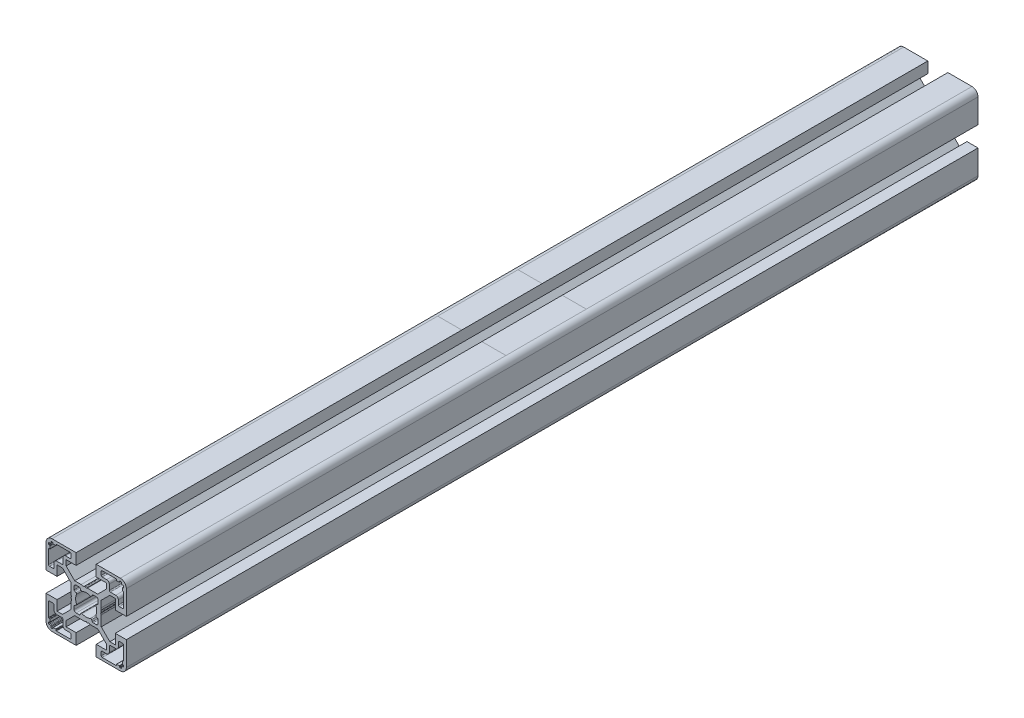
SolidWorks part; units mm, degrees
material "6063-T5"
ref_plane "Front Plane" through (0, 0, 0) normal (0, 0, 1) x (1, 0, 0)
ref_plane "Top Plane" through (0, 0, 0) normal (0, 1, 0) x (1, 0, 0)
ref_plane "Right Plane" through (0, 0, 0) normal (1, 0, 0) x (0, 0, -1)
ref_plane "Plan1" through (0, 0, 50) normal (0, 0, 1) x (1, 0, 0)
sketch "Esquisse1" plane through (0, 0, 50) normal (0, 0, 1) x (1, 0, 0)
  line L0 (-11.2645, -4.6769) -> (-11.2645, 2.1231)
  line L1 (-10.7645, 2.6231) -> (-9.0645, 2.6231)
  line L2 (-8.5645, 2.1231) -> (-8.5645, -0.0769)
  line L3 (-7.2645, -1.3769) -> (-4.5645, -1.3769)
  line L4 (-4.0645, -1.8769) -> (-4.0645, -4.5769)
  line L5 (-2.7645, -5.8769) -> (-0.5645, -5.8769)
  line L6 (-0.0645, -6.3769) -> (-0.0645, -8.0769)
  line L7 (-0.5645, -8.5769) -> (-7.3645, -8.5769)
  line L8 (-7.5645, -8.3769) -> (-7.5645, -8.0769)
  line L9 (-7.7645, -7.8769) -> (-8.9645, -7.8769)
  line L10 (-9.1645, -8.0769) -> (-9.1645, -8.3769)
  line L11 (-9.3645, -8.5769) -> (-9.8645, -8.5769)
  line L12 (-10.1645, -8.2769) -> (-10.1645, -7.7769)
  line L13 (-10.4645, -7.4769) -> (-10.9645, -7.4769)
  line L14 (-11.2645, -7.1769) -> (-11.2645, -6.6769)
  line L15 (-11.0645, -6.4769) -> (-10.7645, -6.4769)
  line L16 (-10.5645, -6.2769) -> (-10.5645, -5.0769)
  line L17 (-10.7645, -4.8769) -> (-11.0645, -4.8769)
  line L18 (14.9355, -8.0769) -> (14.9355, -6.3769)
  line L19 (15.4355, -5.8769) -> (17.6355, -5.8769)
  line L20 (18.9355, -4.5769) -> (18.9355, -1.8769)
  line L21 (19.4355, -1.3769) -> (22.1355, -1.3769)
  line L22 (23.4355, -0.0769) -> (23.4355, 2.1231)
  line L23 (23.9355, 2.6231) -> (25.6355, 2.6231)
  line L24 (26.1355, 2.1231) -> (26.1355, -4.6769)
  line L25 (25.9355, -4.8769) -> (25.6355, -4.8769)
  line L26 (25.4355, -5.0769) -> (25.4355, -6.2769)
  line L27 (25.6355, -6.4769) -> (25.9355, -6.4769)
  line L28 (26.1355, -6.6769) -> (26.1355, -7.1769)
  line L29 (25.8355, -7.4769) -> (25.3355, -7.4769)
  line L30 (25.0355, -7.7769) -> (25.0355, -8.2769)
  line L31 (24.7355, -8.5769) -> (24.2355, -8.5769)
  line L32 (24.0355, -8.3769) -> (24.0355, -8.0769)
  line L33 (23.8355, -7.8769) -> (22.6355, -7.8769)
  line L34 (22.4355, -8.0769) -> (22.4355, -8.3769)
  line L35 (22.2355, -8.5769) -> (15.4355, -8.5769)
  line L36 (-12.5645, 27.1231) -> (-12.5645, 15.1231)
  line L37 (-12.5645, 15.1231) -> (-7.0645, 15.1231)
  line L38 (-7.0645, 15.1231) -> (-7.0645, 20.1231)
  line L39 (-7.0645, 20.1231) -> (-4.3322, 20.1231)
  line L40 (-4.3322, 20.1231) -> (-0.0645, 15.8553)
  line L41 (-0.0645, 15.8553) -> (-0.0645, 10.7767)
  line L42 (0.0025, 10.5267) -> (0.2355, 10.1231)
  line L43 (0.2355, 10.1231) -> (0.0025, 9.7195)
  line L44 (0.0025, 9.2195) -> (0.1846, 8.9042)
  line L45 (0.1846, 8.9042) -> (-0.0645, 7.6231)
  line L46 (-0.0645, 7.6231) -> (-0.0645, 4.3908)
  line L47 (-0.0645, 4.3908) -> (-4.3322, 0.1231)
  line L48 (-4.3322, 0.1231) -> (-7.0645, 0.1231)
  line L49 (-7.0645, 0.1231) -> (-7.0645, 5.1231)
  line L50 (-7.0645, 5.1231) -> (-12.5645, 5.1231)
  line L51 (-12.5645, 5.1231) -> (-12.5645, -6.8769)
  line L52 (-9.5645, -9.8769) -> (2.4355, -9.8769)
  line L53 (2.4355, -9.8769) -> (2.4355, -4.3769)
  line L54 (2.4355, -4.3769) -> (-2.5645, -4.3769)
  line L55 (-2.5645, -4.3769) -> (-2.5645, -1.6447)
  line L56 (-2.5645, -1.6447) -> (1.7033, 2.6231)
  line L57 (1.7033, 2.6231) -> (6.7819, 2.6231)
  line L58 (7.0319, 2.6901) -> (7.4355, 2.9231)
  line L59 (7.4355, 2.9231) -> (7.8391, 2.6901)
  line L60 (8.3391, 2.6901) -> (8.6544, 2.8721)
  line L61 (8.6544, 2.8721) -> (9.9355, 2.6231)
  line L62 (9.9355, 2.6231) -> (13.1678, 2.6231)
  line L63 (13.1678, 2.6231) -> (17.4355, -1.6447)
  line L64 (17.4355, -1.6447) -> (17.4355, -4.3769)
  line L65 (17.4355, -4.3769) -> (12.4355, -4.3769)
  line L66 (12.4355, -4.3769) -> (12.4355, -9.8769)
  line L67 (12.4355, -9.8769) -> (24.4355, -9.8769)
  line L68 (27.4355, -6.8769) -> (27.4355, 5.1231)
  line L69 (27.4355, 5.1231) -> (21.9355, 5.1231)
  line L70 (21.9355, 5.1231) -> (21.9355, 0.1231)
  line L71 (21.9355, 0.1231) -> (19.2033, 0.1231)
  line L72 (19.2033, 0.1231) -> (14.9355, 4.3908)
  line L73 (14.9355, 4.3908) -> (14.9355, 9.4695)
  line L74 (14.8686, 9.7195) -> (14.6355, 10.1231)
  line L75 (14.6355, 10.1231) -> (14.8686, 10.5267)
  line L76 (14.8686, 11.0267) -> (14.6865, 11.342)
  line L77 (14.6865, 11.342) -> (14.9355, 12.6231)
  line L78 (14.9355, 12.6231) -> (14.9355, 15.8553)
  line L79 (14.9355, 15.8553) -> (19.2033, 20.1231)
  line L80 (19.2033, 20.1231) -> (21.9355, 20.1231)
  line L81 (21.9355, 20.1231) -> (21.9355, 15.1231)
  line L82 (21.9355, 15.1231) -> (27.4355, 15.1231)
  line L83 (27.4355, 15.1231) -> (27.4355, 27.1231)
  line L84 (24.4355, 30.1231) -> (12.4355, 30.1231)
  line L85 (12.4355, 30.1231) -> (12.4355, 24.6231)
  line L86 (12.4355, 24.6231) -> (17.4355, 24.6231)
  line L87 (17.4355, 24.6231) -> (17.4355, 21.8908)
  line L88 (17.4355, 21.8908) -> (13.1678, 17.6231)
  line L89 (13.1678, 17.6231) -> (8.0891, 17.6231)
  line L90 (7.8391, 17.5561) -> (7.4355, 17.3231)
  line L91 (7.4355, 17.3231) -> (7.0319, 17.5561)
  line L92 (6.5319, 17.5561) -> (6.2167, 17.3741)
  line L93 (6.2167, 17.3741) -> (4.9355, 17.6231)
  line L94 (4.9355, 17.6231) -> (1.7033, 17.6231)
  line L95 (1.7033, 17.6231) -> (-2.5645, 21.8908)
  line L96 (-2.5645, 21.8908) -> (-2.5645, 24.6231)
  line L97 (-2.5645, 24.6231) -> (2.4355, 24.6231)
  line L98 (2.4355, 24.6231) -> (2.4355, 30.1231)
  line L99 (2.4355, 30.1231) -> (-9.5645, 30.1231)
  line L100 (14.9355, 26.6231) -> (14.9355, 28.3231)
  line L101 (15.4355, 28.8231) -> (22.2355, 28.8231)
  line L102 (22.4355, 28.6231) -> (22.4355, 28.3231)
  line L103 (22.6355, 28.1231) -> (23.8355, 28.1231)
  line L104 (24.0355, 28.3231) -> (24.0355, 28.6231)
  line L105 (24.2355, 28.8231) -> (24.7355, 28.8231)
  line L106 (25.0355, 28.5231) -> (25.0355, 28.0231)
  line L107 (25.3355, 27.7231) -> (25.8355, 27.7231)
  line L108 (26.1355, 27.4231) -> (26.1355, 26.9231)
  line L109 (25.9355, 26.7231) -> (25.6355, 26.7231)
  line L110 (25.4355, 26.5231) -> (25.4355, 25.3231)
  line L111 (25.6355, 25.1231) -> (25.9355, 25.1231)
  line L112 (26.1355, 24.9231) -> (26.1355, 18.1231)
  line L113 (25.6355, 17.6231) -> (23.9355, 17.6231)
  line L114 (23.4355, 18.1231) -> (23.4355, 20.3231)
  line L115 (22.1355, 21.6231) -> (19.4355, 21.6231)
  line L116 (18.9355, 22.1231) -> (18.9355, 24.8231)
  line L117 (17.6355, 26.1231) -> (15.4355, 26.1231)
  line L118 (-11.2645, 18.1231) -> (-11.2645, 24.9231)
  line L119 (-11.0645, 25.1231) -> (-10.7645, 25.1231)
  line L120 (-10.5645, 25.3231) -> (-10.5645, 26.5231)
  line L121 (-10.7645, 26.7231) -> (-11.0645, 26.7231)
  line L122 (-11.2645, 26.9231) -> (-11.2645, 27.4231)
  line L123 (-10.9645, 27.7231) -> (-10.4645, 27.7231)
  line L124 (-10.1645, 28.0231) -> (-10.1645, 28.5231)
  line L125 (-9.8645, 28.8231) -> (-9.3645, 28.8231)
  line L126 (-9.1645, 28.6231) -> (-9.1645, 28.3231)
  line L127 (-8.9645, 28.1231) -> (-7.7645, 28.1231)
  line L128 (-7.5645, 28.3231) -> (-7.5645, 28.6231)
  line L129 (-7.3645, 28.8231) -> (-0.5645, 28.8231)
  line L130 (-0.0645, 28.3231) -> (-0.0645, 26.6231)
  line L131 (-0.5645, 26.1231) -> (-2.7645, 26.1231)
  line L132 (-4.0645, 24.8231) -> (-4.0645, 22.1231)
  line L133 (-4.5645, 21.6231) -> (-7.2645, 21.6231)
  line L134 (-8.5645, 20.3231) -> (-8.5645, 18.1231)
  line L135 (-9.0645, 17.6231) -> (-10.7645, 17.6231)
  line L136 (10.9262, 16.1231) -> (12.4355, 16.1231)
  line L137 (13.4355, 15.1231) -> (13.4355, 13.6138)
  line L138 (13.1703, 13.1723) -> (12.4933, 12.8123)
  line L139 (12.4933, 7.4338) -> (13.1703, 7.0739)
  line L140 (13.4355, 6.6324) -> (13.4355, 5.1231)
  line L141 (12.4355, 4.1231) -> (10.9262, 4.1231)
  line L142 (10.4848, 4.3883) -> (10.1248, 5.0654)
  line L143 (4.7463, 5.0654) -> (4.3863, 4.3883)
  line L144 (3.9449, 4.1231) -> (2.4355, 4.1231)
  line L145 (1.4355, 5.1231) -> (1.4355, 6.6324)
  line L146 (1.7008, 7.0739) -> (2.3778, 7.4338)
  line L147 (2.3778, 12.8123) -> (1.7008, 13.1723)
  line L148 (1.4355, 13.6138) -> (1.4355, 15.1231)
  line L149 (2.4355, 16.1231) -> (3.9449, 16.1231)
  line L150 (4.3863, 15.8578) -> (4.7463, 15.1808)
  line L151 (10.1248, 15.1808) -> (10.4848, 15.8578)
  arc A0 (-11.2645, 2.1231) -> (-10.7645, 2.6231) centre (-10.7645, 2.1231) cw
  arc A1 (-9.0645, 2.6231) -> (-8.5645, 2.1231) centre (-9.0645, 2.1231) cw
  arc A2 (-8.5645, -0.0769) -> (-7.2645, -1.3769) centre (-7.2645, -0.0769) ccw
  arc A3 (-4.5645, -1.3769) -> (-4.0645, -1.8769) centre (-4.5645, -1.8769) cw
  arc A4 (-4.0645, -4.5769) -> (-2.7645, -5.8769) centre (-2.7645, -4.5769) ccw
  arc A5 (-0.5645, -5.8769) -> (-0.0645, -6.3769) centre (-0.5645, -6.3769) cw
  arc A6 (-0.0645, -8.0769) -> (-0.5645, -8.5769) centre (-0.5645, -8.0769) cw
  arc A7 (-7.3645, -8.5769) -> (-7.5645, -8.3769) centre (-7.3645, -8.3769) cw
  arc A8 (-7.5645, -8.0769) -> (-7.7645, -7.8769) centre (-7.7645, -8.0769) ccw
  arc A9 (-8.9645, -7.8769) -> (-9.1645, -8.0769) centre (-8.9645, -8.0769) ccw
  arc A10 (-9.1645, -8.3769) -> (-9.3645, -8.5769) centre (-9.3645, -8.3769) cw
  arc A11 (-9.8645, -8.5769) -> (-10.1645, -8.2769) centre (-9.8645, -8.2769) cw
  arc A12 (-10.1645, -7.7769) -> (-10.4645, -7.4769) centre (-10.4645, -7.7769) ccw
  arc A13 (-10.9645, -7.4769) -> (-11.2645, -7.1769) centre (-10.9645, -7.1769) cw
  arc A14 (-11.2645, -6.6769) -> (-11.0645, -6.4769) centre (-11.0645, -6.6769) cw
  arc A15 (-10.7645, -6.4769) -> (-10.5645, -6.2769) centre (-10.7645, -6.2769) ccw
  arc A16 (-10.5645, -5.0769) -> (-10.7645, -4.8769) centre (-10.7645, -5.0769) ccw
  arc A17 (-11.0645, -4.8769) -> (-11.2645, -4.6769) centre (-11.0645, -4.6769) cw
  arc A18 (14.9355, -6.3769) -> (15.4355, -5.8769) centre (15.4355, -6.3769) cw
  arc A19 (17.6355, -5.8769) -> (18.9355, -4.5769) centre (17.6355, -4.5769) ccw
  arc A20 (18.9355, -1.8769) -> (19.4355, -1.3769) centre (19.4355, -1.8769) cw
  arc A21 (22.1355, -1.3769) -> (23.4355, -0.0769) centre (22.1355, -0.0769) ccw
  arc A22 (23.4355, 2.1231) -> (23.9355, 2.6231) centre (23.9355, 2.1231) cw
  arc A23 (25.6355, 2.6231) -> (26.1355, 2.1231) centre (25.6355, 2.1231) cw
  arc A24 (26.1355, -4.6769) -> (25.9355, -4.8769) centre (25.9355, -4.6769) cw
  arc A25 (25.6355, -4.8769) -> (25.4355, -5.0769) centre (25.6355, -5.0769) ccw
  arc A26 (25.4355, -6.2769) -> (25.6355, -6.4769) centre (25.6355, -6.2769) ccw
  arc A27 (25.9355, -6.4769) -> (26.1355, -6.6769) centre (25.9355, -6.6769) cw
  arc A28 (26.1355, -7.1769) -> (25.8355, -7.4769) centre (25.8355, -7.1769) cw
  arc A29 (25.3355, -7.4769) -> (25.0355, -7.7769) centre (25.3355, -7.7769) ccw
  arc A30 (25.0355, -8.2769) -> (24.7355, -8.5769) centre (24.7355, -8.2769) cw
  arc A31 (24.2355, -8.5769) -> (24.0355, -8.3769) centre (24.2355, -8.3769) cw
  arc A32 (24.0355, -8.0769) -> (23.8355, -7.8769) centre (23.8355, -8.0769) ccw
  arc A33 (22.6355, -7.8769) -> (22.4355, -8.0769) centre (22.6355, -8.0769) ccw
  arc A34 (22.4355, -8.3769) -> (22.2355, -8.5769) centre (22.2355, -8.3769) cw
  arc A35 (15.4355, -8.5769) -> (14.9355, -8.0769) centre (15.4355, -8.0769) cw
  arc A36 (-9.5645, 30.1231) -> (-12.5645, 27.1231) centre (-9.5645, 27.1231) ccw
  arc A37 (-0.0645, 10.7767) -> (0.0025, 10.5267) centre (0.4355, 10.7767) ccw
  arc A38 (0.0025, 9.7195) -> (0.0025, 9.2195) centre (0.4355, 9.4695) ccw
  arc A39 (-12.5645, -6.8769) -> (-9.5645, -9.8769) centre (-9.5645, -6.8769) ccw
  arc A40 (6.7819, 2.6231) -> (7.0319, 2.6901) centre (6.7819, 3.1231) ccw
  arc A41 (7.8391, 2.6901) -> (8.3391, 2.6901) centre (8.0891, 3.1231) ccw
  arc A42 (24.4355, -9.8769) -> (27.4355, -6.8769) centre (24.4355, -6.8769) ccw
  arc A43 (14.9355, 9.4695) -> (14.8686, 9.7195) centre (14.4355, 9.4695) ccw
  arc A44 (14.8686, 10.5267) -> (14.8686, 11.0267) centre (14.4355, 10.7767) ccw
  arc A45 (27.4355, 27.1231) -> (24.4355, 30.1231) centre (24.4355, 27.1231) ccw
  arc A46 (8.0891, 17.6231) -> (7.8391, 17.5561) centre (8.0891, 17.1231) ccw
  arc A47 (7.0319, 17.5561) -> (6.5319, 17.5561) centre (6.7819, 17.1231) ccw
  arc A48 (14.9355, 28.3231) -> (15.4355, 28.8231) centre (15.4355, 28.3231) cw
  arc A49 (22.2355, 28.8231) -> (22.4355, 28.6231) centre (22.2355, 28.6231) cw
  arc A50 (22.4355, 28.3231) -> (22.6355, 28.1231) centre (22.6355, 28.3231) ccw
  arc A51 (23.8355, 28.1231) -> (24.0355, 28.3231) centre (23.8355, 28.3231) ccw
  arc A52 (24.0355, 28.6231) -> (24.2355, 28.8231) centre (24.2355, 28.6231) cw
  arc A53 (24.7355, 28.8231) -> (25.0355, 28.5231) centre (24.7355, 28.5231) cw
  arc A54 (25.0355, 28.0231) -> (25.3355, 27.7231) centre (25.3355, 28.0231) ccw
  arc A55 (25.8355, 27.7231) -> (26.1355, 27.4231) centre (25.8355, 27.4231) cw
  arc A56 (26.1355, 26.9231) -> (25.9355, 26.7231) centre (25.9355, 26.9231) cw
  arc A57 (25.6355, 26.7231) -> (25.4355, 26.5231) centre (25.6355, 26.5231) ccw
  arc A58 (25.4355, 25.3231) -> (25.6355, 25.1231) centre (25.6355, 25.3231) ccw
  arc A59 (25.9355, 25.1231) -> (26.1355, 24.9231) centre (25.9355, 24.9231) cw
  arc A60 (26.1355, 18.1231) -> (25.6355, 17.6231) centre (25.6355, 18.1231) cw
  arc A61 (23.9355, 17.6231) -> (23.4355, 18.1231) centre (23.9355, 18.1231) cw
  arc A62 (23.4355, 20.3231) -> (22.1355, 21.6231) centre (22.1355, 20.3231) ccw
  arc A63 (19.4355, 21.6231) -> (18.9355, 22.1231) centre (19.4355, 22.1231) cw
  arc A64 (18.9355, 24.8231) -> (17.6355, 26.1231) centre (17.6355, 24.8231) ccw
  arc A65 (15.4355, 26.1231) -> (14.9355, 26.6231) centre (15.4355, 26.6231) cw
  arc A66 (-11.2645, 24.9231) -> (-11.0645, 25.1231) centre (-11.0645, 24.9231) cw
  arc A67 (-10.7645, 25.1231) -> (-10.5645, 25.3231) centre (-10.7645, 25.3231) ccw
  arc A68 (-10.5645, 26.5231) -> (-10.7645, 26.7231) centre (-10.7645, 26.5231) ccw
  arc A69 (-11.0645, 26.7231) -> (-11.2645, 26.9231) centre (-11.0645, 26.9231) cw
  arc A70 (-11.2645, 27.4231) -> (-10.9645, 27.7231) centre (-10.9645, 27.4231) cw
  arc A71 (-10.4645, 27.7231) -> (-10.1645, 28.0231) centre (-10.4645, 28.0231) ccw
  arc A72 (-10.1645, 28.5231) -> (-9.8645, 28.8231) centre (-9.8645, 28.5231) cw
  arc A73 (-9.3645, 28.8231) -> (-9.1645, 28.6231) centre (-9.3645, 28.6231) cw
  arc A74 (-9.1645, 28.3231) -> (-8.9645, 28.1231) centre (-8.9645, 28.3231) ccw
  arc A75 (-7.7645, 28.1231) -> (-7.5645, 28.3231) centre (-7.7645, 28.3231) ccw
  arc A76 (-7.5645, 28.6231) -> (-7.3645, 28.8231) centre (-7.3645, 28.6231) cw
  arc A77 (-0.5645, 28.8231) -> (-0.0645, 28.3231) centre (-0.5645, 28.3231) cw
  arc A78 (-0.0645, 26.6231) -> (-0.5645, 26.1231) centre (-0.5645, 26.6231) cw
  arc A79 (-2.7645, 26.1231) -> (-4.0645, 24.8231) centre (-2.7645, 24.8231) ccw
  arc A80 (-4.0645, 22.1231) -> (-4.5645, 21.6231) centre (-4.5645, 22.1231) cw
  arc A81 (-7.2645, 21.6231) -> (-8.5645, 20.3231) centre (-7.2645, 20.3231) ccw
  arc A82 (-8.5645, 18.1231) -> (-9.0645, 17.6231) centre (-9.0645, 18.1231) cw
  arc A83 (-10.7645, 17.6231) -> (-11.2645, 18.1231) centre (-10.7645, 18.1231) cw
  arc A84 (12.4355, 16.1231) -> (13.4355, 15.1231) centre (12.4355, 15.1231) cw
  arc A85 (13.4355, 13.6138) -> (13.1703, 13.1723) centre (12.9355, 13.6138) cw
  arc A86 (12.4933, 12.8123) -> (12.2678, 12.1754) centre (12.728, 12.3708) ccw
  arc A87 (12.2678, 12.1754) -> (12.2678, 8.0708) centre (7.4355, 10.1231) cw
  arc A88 (12.2678, 8.0708) -> (12.4933, 7.4338) centre (12.728, 7.8753) ccw
  arc A89 (13.1703, 7.0739) -> (13.4355, 6.6324) centre (12.9355, 6.6324) cw
  arc A90 (13.4355, 5.1231) -> (12.4355, 4.1231) centre (12.4355, 5.1231) cw
  arc A91 (10.9262, 4.1231) -> (10.4848, 4.3883) centre (10.9262, 4.6231) cw
  arc A92 (10.1248, 5.0654) -> (9.4878, 5.2908) centre (9.6833, 4.8306) ccw
  arc A93 (9.4878, 5.2908) -> (5.3832, 5.2908) centre (7.4355, 10.1231) cw
  arc A94 (5.3832, 5.2908) -> (4.7463, 5.0654) centre (5.1878, 4.8306) ccw
  arc A95 (4.3863, 4.3883) -> (3.9449, 4.1231) centre (3.9449, 4.6231) cw
  arc A96 (2.4355, 4.1231) -> (1.4355, 5.1231) centre (2.4355, 5.1231) cw
  arc A97 (1.4355, 6.6324) -> (1.7008, 7.0739) centre (1.9355, 6.6324) cw
  arc A98 (2.3778, 7.4338) -> (2.6033, 8.0708) centre (2.1431, 7.8753) ccw
  arc A99 (2.6033, 8.0708) -> (2.6033, 12.1754) centre (7.4355, 10.1231) cw
  arc A100 (2.6033, 12.1754) -> (2.3778, 12.8123) centre (2.1431, 12.3708) ccw
  arc A101 (1.7008, 13.1723) -> (1.4355, 13.6138) centre (1.9355, 13.6138) cw
  arc A102 (1.4355, 15.1231) -> (2.4355, 16.1231) centre (2.4355, 15.1231) cw
  arc A103 (3.9449, 16.1231) -> (4.3863, 15.8578) centre (3.9449, 15.6231) cw
  arc A104 (4.7463, 15.1808) -> (5.3832, 14.9553) centre (5.1878, 15.4155) ccw
  arc A105 (5.3832, 14.9553) -> (9.4878, 14.9553) centre (7.4355, 10.1231) cw
  arc A106 (9.4878, 14.9553) -> (10.1248, 15.1808) centre (9.6833, 15.4155) ccw
  arc A107 (10.4848, 15.8578) -> (10.9262, 16.1231) centre (10.9262, 15.6231) cw
extrude "Boss.-Extru.1" add sketch "Esquisse1" against normal blind 424
sketch "Esquisse2" plane through (0, 30.1231, 0) normal (0, 1, 0) x (1, 0, 0)
  line L0 (-12.5645, 374) -> (-12.5645, -50) construction
  line L1 (-12.5645, 182) -> (27.4355, 182)
  line L2 (-12.5645, 182) -> (-12.5645, 142)
  line L3 (-12.5645, 142) -> (27.4355, 142)
  line L4 (27.4355, 182) -> (27.4355, 142)
  line L5 (27.4355, 374) -> (27.4355, -50) construction
  line L6 (-12.5645, 162) -> (27.4355, 162) construction
  dimension "D1" = 40
split line "Ligne de séparation1"
